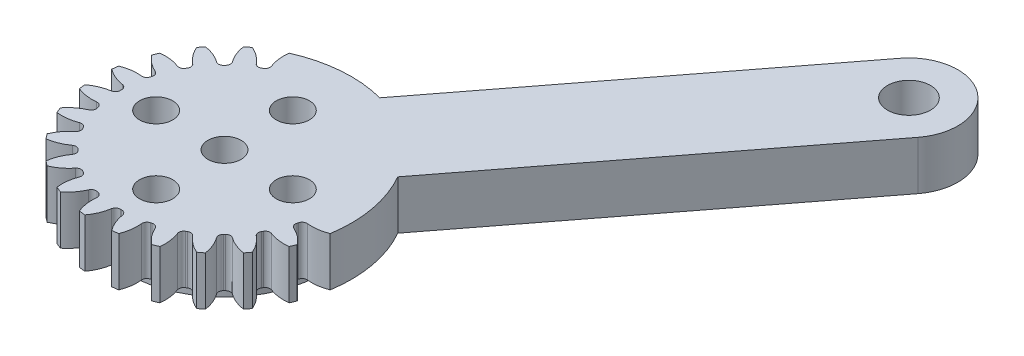
SolidWorks part; units mm, degrees
ref_plane "Front Plane" through (0, 0, 0) normal (0, 0, 1) x (1, 0, 0)
ref_plane "Top Plane" through (0, 0, 0) normal (0, 1, 0) x (1, 0, 0)
ref_plane "Right Plane" through (0, 0, 0) normal (1, 0, 0) x (0, 0, -1)
sketch "Sketch2" plane through (0, 0, 0) normal (0, 1, 0) x (1, 0, 0)
  circle A0 centre (0, 0) radius 13
  circle A1 centre (0, 0) radius 1.7
  dimension "D1" = 3.4
  dimension "D2" = 26
extrude "Boss-Extrude1" add sketch "Sketch2" along normal blind 5
sketch "Sketch3" plane through (0, 5, 0) normal (0, 1, 0) x (1, 0, 0)
  line L0 (0, 0) -> (0, 13) construction
  line L1 (-0.5275, 10.5869) -> (0, 0) construction
  line L2 (0, 9.6865) -> (14.5717, -30.349) construction
  arc A0 (0.5275, 10.5869) -> (-0.5275, 10.5869) centre (0, 0) ccw
  arc A1 (0.8347, 11.9709) -> (-0.8347, 11.9709) centre (0, 0) ccw construction
  arc A2 (1.3791, 12.9266) -> (-1.3791, 12.9266) centre (0, 0) ccw
  circle A3 centre (0, 0) radius 13 construction
  arc A5 (-1.3791, 12.9266) -> (-0.5275, 10.5869) centre (-4.7448, 10.3768) cw
  arc A6 (1.3791, 12.9266) -> (0.5275, 10.5869) centre (4.7448, 10.3768) ccw
  point P16 (-0.7769, 11.821)
  dimension "D1" = 24
  dimension "D2" = 2.4
  dimension "D3" = 20
  dimension "D4" = 1.6708
extrude "Cut-Extrude1" cut sketch "Sketch3" against normal through all
fillet "Fillet1" radius 0.5 2 edges at (0.5275, 2.5, -10.5869) (-0.5275, 2.5, -10.5869)
fillet "圆角1" [suppressed] radius 0.2
pattern_circular "CirPattern1" count 24 over 360 about axis through (0, 0, 0) along (0, 1, 0) of "Cut-Extrude1", "Fillet1", "圆角1"
sketch "草图3" plane through (0, 5, 0) normal (0, 1, 0) x (1, 0, 0)
  circle A0 centre (0, 0) radius 12 construction
  dimension "D1" = 24
sketch "草图4" plane through (0, 5, 0) normal (0, 1, 0) x (1, 0, 0)
  line L0 (-7, 0) -> (7, 0) construction
  circle A1 centre (-7, 0) radius 1.7
  circle A4 centre (0, 7) radius 1.7
  circle A5 centre (7, 0) radius 1.7
  circle A6 centre (0, -7) radius 1.7
  point P13 (0, 0)
  dimension "D3" = 4
  dimension "D2" = 3.4
  dimension "D1" = 14
extrude "切除-拉伸1" cut sketch "草图4" against normal through all
sketch "草图5" plane through (0, 5, 0) normal (0, 1, 0) x (1, 0, 0)
  line L0 (0, 0) -> (30.4381, 39.6677) construction
  line L1 (0.9033, 9.3906) -> (26.4713, 42.7115)
  line L2 (0.9033, 9.3906) -> (8.8369, 3.303)
  line L3 (8.8369, 3.303) -> (34.4048, 36.6239)
  line L5 (0, 0) -> (12, 0) construction
  line L6 (-4.9749, 12.0104) -> (-3.6102, 8.7159)
  line L7 (12.8888, -1.6968) -> (9.3533, -1.2314)
  arc A1 (34.4048, 36.6239) -> (26.4713, 42.7115) centre (30.4381, 39.6677) ccw
  circle A2 centre (30.4381, 39.6677) radius 2.2
  circle A3 centre (0, 0) radius 12 construction
  arc A4 (-4.9749, 12.0104) -> (3.3384, 12.564) centre (0, 0) cw
  arc A5 (-4.6777, 12.1293) -> (-5.269, 11.8843) centre (0, 0) ccw construction
  arc A6 (0.9033, 9.3906) -> (-3.6102, 8.7159) centre (0, 0) ccw
  arc A7 (11.2719, 6.4764) -> (12.8888, -1.6968) centre (0, 0) cw
  arc A8 (12.8431, -2.0136) -> (12.9266, -1.3791) centre (0, 0) ccw construction
  arc A9 (9.3533, -1.2314) -> (8.8369, 3.303) centre (0, 0) ccw
  dimension "D3" = 4.4
  dimension "D1" = 8
  dimension "D2" = 10
  dimension "D4" = 52.5
  dimension "D5" = 50
extrude "凸台-拉伸1" add sketch "草图5" against normal up to surface (5 mm away) contours A6 L1 A4 L6 | L3 A1 L1 L2 A2 | A9 L7 A7 L3 up to face at (-7, 0, 1.7)
sketch "草图6" plane through (0, 0, 0) normal (0, -1, 0) x (-1, 0, 0)
  circle A0 centre (0, 0) radius 10
  circle A1 centre (7, 0) radius 1.7 construction
  circle A2 centre (0, -7) radius 1.7 construction
  circle A3 centre (-7, 0) radius 1.7 construction
  circle A4 centre (0, 0) radius 1.7 construction
  circle A5 centre (0, 7) radius 1.7 construction
  circle A6 centre (0, 0) radius 1.7
  circle A7 centre (0, 7) radius 1.7
  circle A8 centre (-7, 0) radius 1.7
  circle A9 centre (0, -7) radius 1.7
  circle A10 centre (7, 0) radius 1.7
  dimension "D1" = 20
extrude "凸台-拉伸2" add sketch "草图6" along normal blind 1
equation "\"No. of teeth\"= 24"
equation "\"Module\"= 1"
equation "\"Bore diameter\"= 3.4"
equation "\"Pressure angle\"= 20"
equation "\"Outer diameter\"= ( \"No. of teeth\" + 2 ) * \"Module\""
equation "\"Pitch diameter\"= \"No. of teeth\" * \"Module\""
equation "\"Backlash\"= 0.1"
equation "\"Arc length\"= ( ( \"Module\" * pi ) / 2 ) + \"Backlash\""
equation "\"Fillet radius\"= 0.5"
equation "\"Tooth depth\"= IIF ( \"Module\" <= 1.25 , \"Module\" * 2.4 , \"Module\" * 2.25 )"
equation "\"D1@Sketch2\"=\"Bore diameter\""
equation "\"D2@Sketch2\"=\"Outer diameter\""
equation "\"D1@Sketch3\"=\"Pitch diameter\""
equation "\"D2@Sketch3\"=\"Tooth depth\""
equation "\"D3@Sketch3\"=\"Pressure angle\""
equation "\"D4@Sketch3\"=\"Arc length\""
equation "\"D1@Fillet1\"=\"Fillet radius\""
equation "\"D1@CirPattern1\"=\"No. of teeth\""
equation "\"Gear thickness\"=5"
equation "\"D1@Boss-Extrude1\"=\"Gear thickness\""
